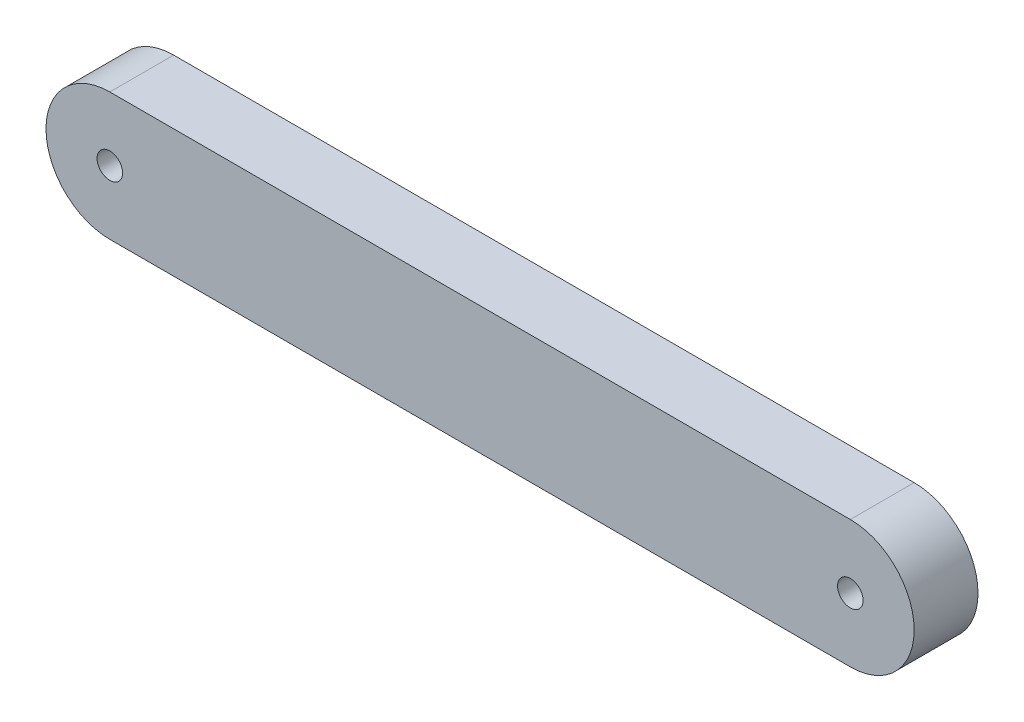
SolidWorks part; units mm, degrees
ref_plane "Front Plane" through (0, 0, 0) normal (0, 0, 1) x (1, 0, 0)
ref_plane "Top Plane" through (0, 0, 0) normal (0, 1, 0) x (1, 0, 0)
ref_plane "Right Plane" through (0, 0, 0) normal (1, 0, 0) x (0, 0, -1)
sketch "Sketch1" plane through (0, 0, 0) normal (0, 0, 1) x (1, 0, 0)
  line L0 (-77.2328, 7.5042) -> (-193.2328, 7.5042) construction
  line L1 (-77.2328, -2.4958) -> (-193.2328, -2.4958)
  line L2 (-77.2328, 17.5042) -> (-193.2328, 17.5042)
  arc A0 (-77.2328, -2.4958) -> (-77.2328, 17.5042) centre (-77.2328, 7.5042) ccw
  arc A1 (-193.2328, 17.5042) -> (-193.2328, -2.4958) centre (-193.2328, 7.5042) ccw
  circle A2 centre (-193.2328, 7.5042) radius 2
  circle A3 centre (-77.2328, 7.5042) radius 2
  point P2 (-135.2328, 7.5042)
  dimension "D2" = 10
  dimension "D1" = 116
extrude "Boss-Extrude1" add sketch "Sketch1" along normal blind 10
